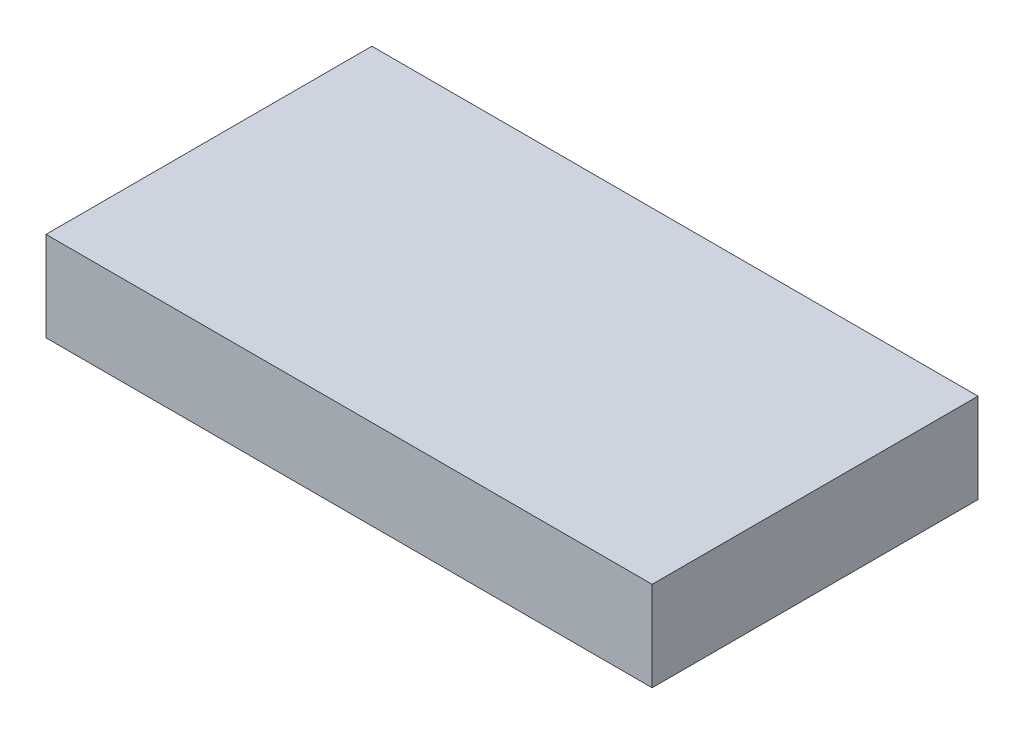
SolidWorks part; units mm, degrees
ref_plane "Front Plane" through (0, 0, 0) normal (0, 0, 1) x (1, 0, 0)
ref_plane "Top Plane" through (0, 0, 0) normal (0, 1, 0) x (1, 0, 0)
ref_plane "Right Plane" through (0, 0, 0) normal (1, 0, 0) x (0, 0, -1)
sketch "Sketch1" plane through (0, 0, 0) normal (0, 1, 0) x (1, 0, 0)
  line L1 (0, 0) -> (37.2, 0)
  line L2 (0, 0) -> (0, 20)
  line L3 (0, 20) -> (37.2, 20)
  line L4 (37.2, 0) -> (37.2, 20)
  dimension "D1" = 37.2
  dimension "D2" = 20
extrude "Boss-Extrude1" add sketch "Sketch1" along normal blind 5.5
